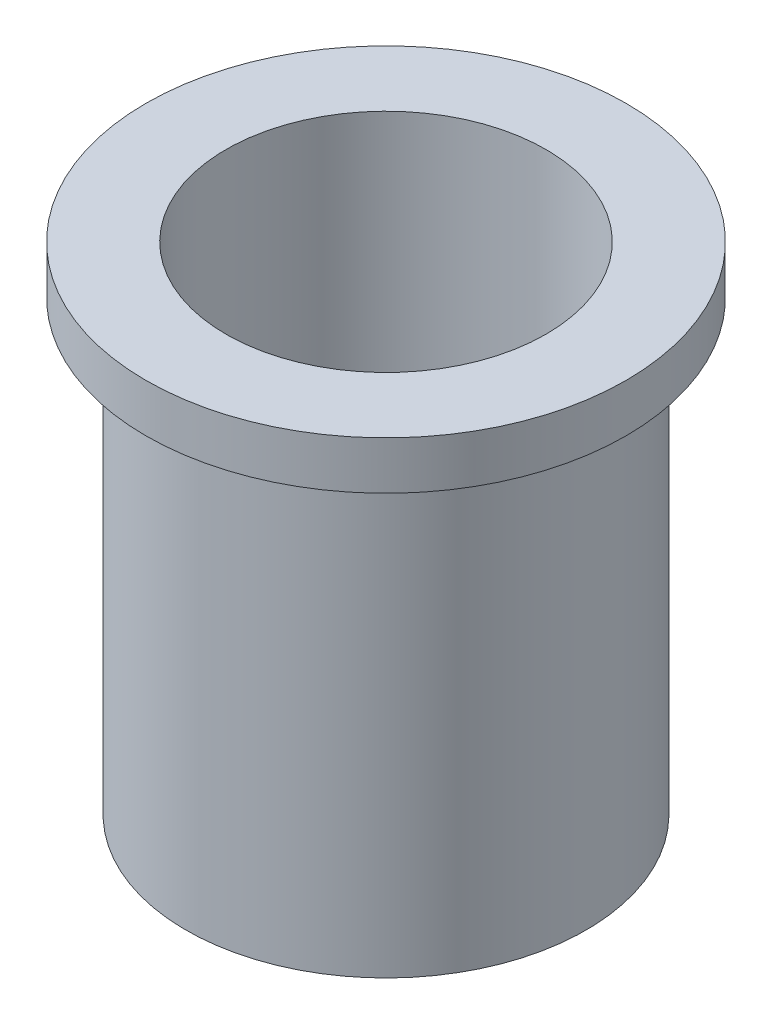
SolidWorks part; units mm, degrees
material "Brass"
ref_plane "Front Plane" through (0, 0, 0) normal (0, 0, 1) x (1, 0, 0)
ref_plane "Top Plane" through (0, 0, 0) normal (0, 1, 0) x (1, 0, 0)
ref_plane "Right Plane" through (0, 0, 0) normal (1, 0, 0) x (0, 0, -1)
sketch "Sketch1" plane through (0, 0, 0) normal (0, 0, 1) x (1, 0, 0)
  line L0 (0, 40.3469) -> (0, -49.2476) construction
  line L1 (12.5, 6.1081) -> (15, 6.1081)
  line L2 (15, 6.1081) -> (15, 9.1081)
  line L3 (15, 9.1081) -> (0, 9.1081)
  line L4 (12.5, 6.1081) -> (12.5, -21.8919)
  line L5 (12.5, -21.8919) -> (0, -21.8919)
  line L6 (0, 9.1081) -> (0, -21.8919)
  dimension "D1" = 28
  dimension "D2" = 12.5
  dimension "D3" = 3
  dimension "D4" = 15
  dimension "D5" = 31
revolve "Revolve1" add sketch "Sketch1" angle 360 about L0
sketch "Sketch2" plane through (0, -21.8919, 0) normal (0, -1, 0) x (1, 0, 0)
  circle A0 centre (0, 0) radius 10
  dimension "D1" = 20
extrude "Cut-Extrude1" cut sketch "Sketch2" against normal through all
